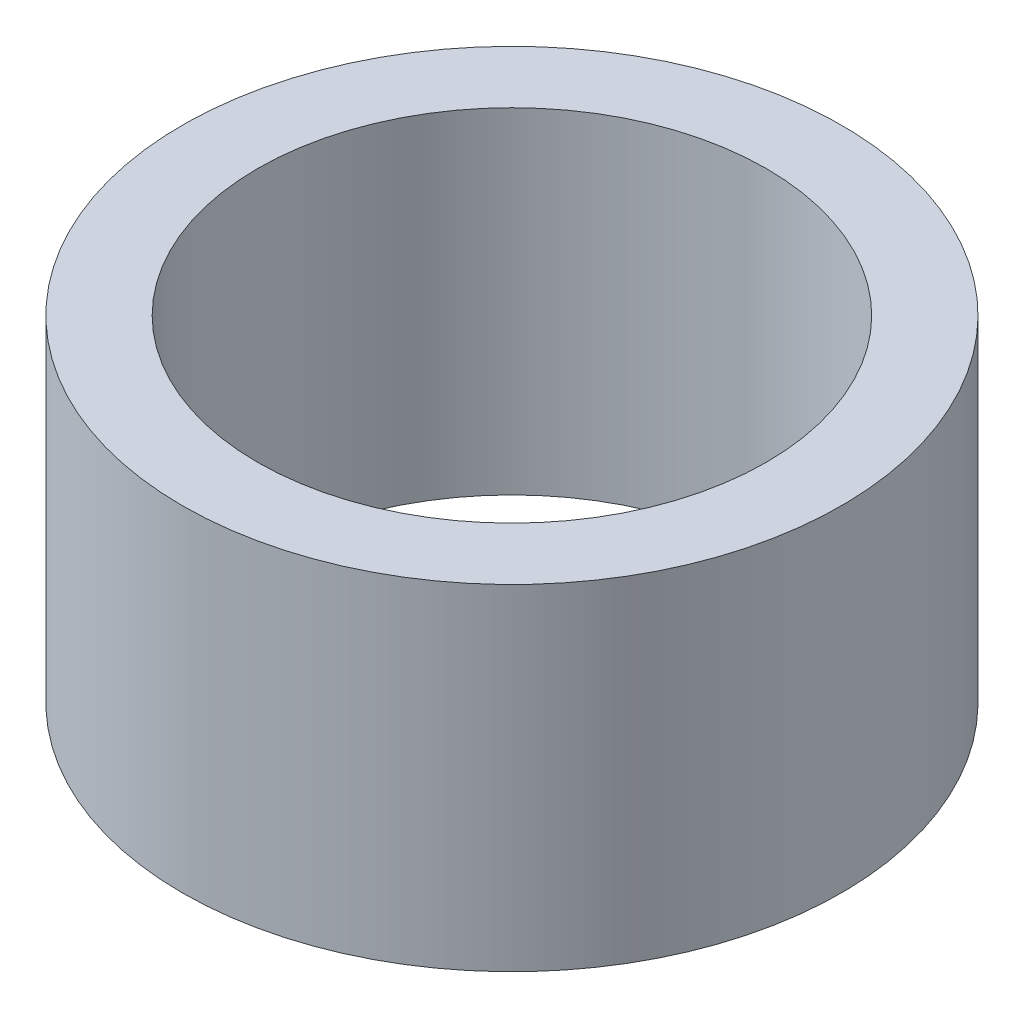
SolidWorks part; units mm, degrees
ref_plane "Front Plane" through (0, 0, 0) normal (0, 0, 1) x (1, 0, 0)
ref_plane "Top Plane" through (0, 0, 0) normal (0, 1, 0) x (1, 0, 0)
ref_plane "Right Plane" through (0, 0, 0) normal (1, 0, 0) x (0, 0, -1)
sketch "Sketch1" plane through (0, 0, 0) normal (0, 1, 0) x (1, 0, 0)
  circle A0 centre (0, 0) radius 28.5
  circle A1 centre (0, 0) radius 22
  dimension "D1" = 44
  dimension "D2" = 57
sketch "Sketch2" plane through (0, 0, 0) normal (0, 1, 0) x (1, 0, 0)
extrude "Boss-Extrude1" add sketch "Sketch1" along normal blind 29
